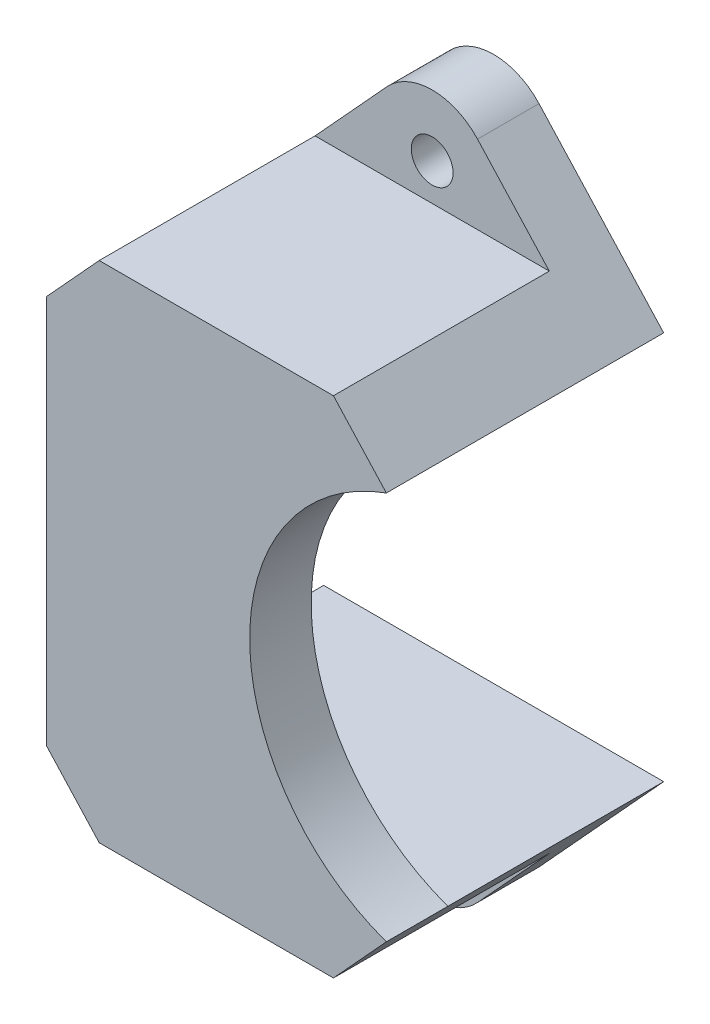
SolidWorks part; units mm, degrees
ref_plane "Front Plane" through (0, 0, 0) normal (0, 0, 1) x (1, 0, 0)
ref_plane "Top Plane" through (0, 0, 0) normal (0, 1, 0) x (1, 0, 0)
ref_plane "Right Plane" through (0, 0, 0) normal (1, 0, 0) x (0, 0, -1)
sketch "Sketch1" plane through (0, 0, 0) normal (0, 0, 1) x (1, 0, 0)
  line L0 (-24.7605, 0) -> (-17.0549, 0)
  line L5 (-3.6887, 26.8754) -> (-13.8234, 15.8)
  line L6 (3.6887, 26.8754) -> (13.8234, 15.8)
  line L7 (13.8234, 15.8) -> (-13.8234, 15.8)
  line L8 (13.8234, -15.8) -> (-13.8234, -15.8)
  line L9 (3.6887, -26.8754) -> (13.8234, -15.8)
  line L10 (-3.6887, -26.8754) -> (-13.8234, -15.8)
  circle A0 centre (0, 23.5) radius 1.7
  arc A1 (3.6887, 26.8754) -> (-3.6887, 26.8754) centre (0, 23.5) ccw
  arc A2 (3.6887, -26.8754) -> (-3.6887, -26.8754) centre (0, -23.5) cw
  circle A3 centre (0, -23.5) radius 1.7
extrude "Boss-Extrude1" add sketch "Sketch1" along normal blind 5 contours L6 A1 L5 L7 A0 | A2 L9 L8 L10 A3
sketch "Sketch2" plane through (0, 0, 5) normal (0, 0, 1) x (1, 0, 0)
  line L0 (-13.8234, 15.8) -> (13.8234, 15.8)
  line L1 (3.6887, 26.8754) -> (13.8234, 15.8) construction
  line L2 (13.8234, 15.8) -> (-13.8234, 15.8) construction
  line L3 (-13.8234, 15.8) -> (-9.5226, 20.5)
  line L4 (-3.6887, 26.8754) -> (-13.8234, 15.8) construction
  line L5 (-38.5, 20.5) -> (-9.5226, 20.5) construction
  line L6 (-9.5226, 20.5) -> (9.5226, 20.5)
  line L7 (9.5226, 20.5) -> (13.8234, 15.8)
  line L8 (-24.7605, 0) -> (-15.9728, 0)
  line L9 (-24.7605, 12) -> (-24.7605, -12) construction
  line L10 (9.5226, -20.5) -> (13.8234, -15.8)
  line L11 (-9.5226, -20.5) -> (9.5226, -20.5)
  line L12 (-13.8234, -15.8) -> (-9.5226, -20.5)
  line L13 (-13.8234, -15.8) -> (13.8234, -15.8)
  line M7 (13.8234, 15.8) -> (3.6887, 26.8754)
  line M9 (-3.6887, 26.8754) -> (-13.8234, 15.8)
  line M10 (-13.8234, 15.8) -> (13.8234, 15.8)
extrude "Boss-Extrude2" add sketch "Sketch2" along normal offset from surface (12.55 mm away) 0.35 contours L13 L12 L11 L10 | L6 M9 M10 M7
sketch "Sketch3" plane through (0, 0, 17.55) normal (0, 0, 1) x (1, 0, 0)
  line L0 (-13.8234, 15.8) -> (-13.8234, -15.8)
  line L1 (-13.8234, -15.8) -> (13.8234, -15.8) construction
  line L2 (-13.8234, -15.8) -> (-9.5226, -20.5) construction
  line L5 (13.8234, 15.8) -> (9.5226, 20.5) construction
  line L6 (13.8234, -15.8) -> (9.5226, -20.5)
  line L7 (9.5226, -20.5) -> (-9.5226, -20.5)
  line L8 (-9.5226, -20.5) -> (-13.8234, -15.8)
  line L9 (-13.8234, 15.8) -> (-9.5226, 20.5)
  line L10 (-9.5226, 20.5) -> (9.5226, 20.5)
  line L11 (9.5226, 20.5) -> (13.8234, 15.8)
  arc A0 (13.8234, 15.8) -> (13.8234, -15.8) centre (19.5, 0) ccw
extrude "Boss-Extrude3" add sketch "Sketch3" along normal blind 5 contours L0 L8 L7 L6 A0 L11 L10 L9
